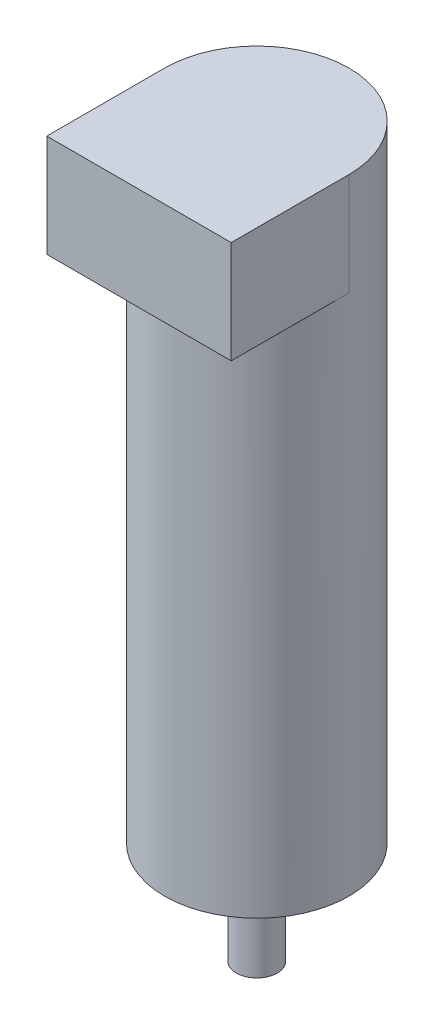
SolidWorks part; units mm, degrees
ref_plane "Front Plane" through (0, 0, 0) normal (0, 0, 1) x (1, 0, 0)
ref_plane "Top Plane" through (0, 0, 0) normal (0, 1, 0) x (1, 0, 0)
ref_plane "Right Plane" through (0, 0, 0) normal (1, 0, 0) x (0, 0, -1)
sketch "Sketch1" plane through (0, 0, 0) normal (0, 1, 0) x (1, 0, 0)
  circle A0 centre (0, 0) radius 18
extrude "Boss-Extrude1" add sketch "Sketch1" along normal blind 102
sketch "Sketch2" plane through (0, 0, 0) normal (0, -1, 0) x (1, 0, 0)
  circle A1 centre (-15, 0) radius 1.5
extrude "Cut-Extrude1" cut sketch "Sketch2" against normal blind 5
pattern_circular "CirPattern1" count 4 over 360 about axis through (0, 0, 0) along (0, 1, 0) of "Cut-Extrude1"
sketch "Sketch3" plane through (0, 0, 0) normal (0, -1, 0) x (1, 0, 0)
  circle A0 centre (0, 0) radius 11
extrude "Boss-Extrude2" add sketch "Sketch3" along normal blind 3
sketch "Sketch4" plane through (0, -3, 0) normal (0, -1, 0) x (1, 0, 0)
  circle A0 centre (0, 0) radius 4
extrude "Boss-Extrude3" add sketch "Sketch4" along normal blind 17
sketch "Sketch5" plane through (0, -20, 0) normal (0, -1, 0) x (1, 0, 0)
  line L0 (-2.6458, -3) -> (2.6458, -3)
  arc A4 (2.6458, -3) -> (-2.6458, -3) centre (0, 0) cw
  point P7 (0, -3)
extrude "Cut-Extrude2" cut sketch "Sketch5" against normal blind 15
sketch "Sketch7" plane through (0, 102, 0) normal (0, 1, 0) x (1, 0, 0)
  line L5 (-18, 0) -> (-18, -23)
  line L6 (18, 0) -> (18, -23)
  line L7 (-18, -23) -> (18, -23)
  circle A1 centre (0, 0) radius 18 construction
  arc A2 (-18, 0) -> (18, 0) centre (0, 0) cw
extrude "Boss-Extrude4" add sketch "Sketch7" along normal blind 20
